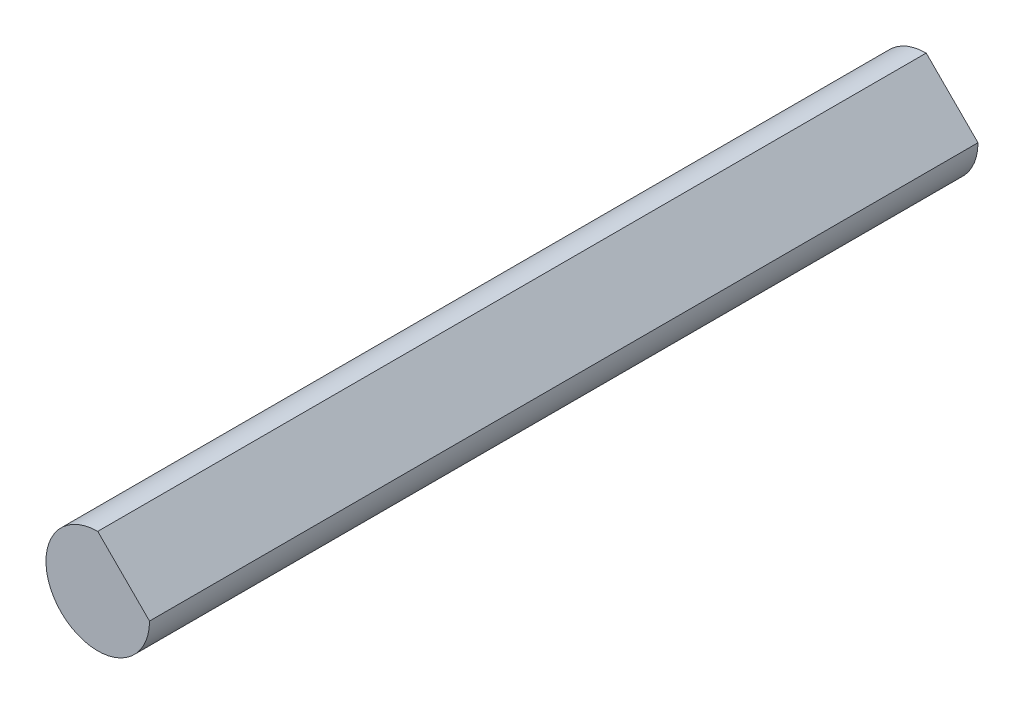
SolidWorks part; units mm, degrees
ref_plane "Front Plane" through (0, 0, 0) normal (0, 0, 1) x (1, 0, 0)
ref_plane "Top Plane" through (0, 0, 0) normal (0, 1, 0) x (1, 0, 0)
ref_plane "Right Plane" through (0, 0, 0) normal (1, 0, 0) x (0, 0, -1)
sketch "Sketch1" plane through (0, 0, 0) normal (0, 0, 1) x (1, 0, 0)
  circle A0 centre (0, 0) radius 3.175
  dimension "D1" = 6.35
extrude "Boss-Extrude1" add sketch "Sketch1" along normal blind 50.8
sketch "Sketch2" plane through (0, 0, 50.8) normal (0, 0, 1) x (1, 0, 0)
  line L0 (0, 3.175) -> (3.175, 0)
  circle A0 centre (0, 0) radius 3.175 construction
  arc A1 (0, 3.175) -> (3.175, 0) centre (0, 0) cw
extrude "Cut-Extrude1" cut sketch "Sketch2" against normal through all
